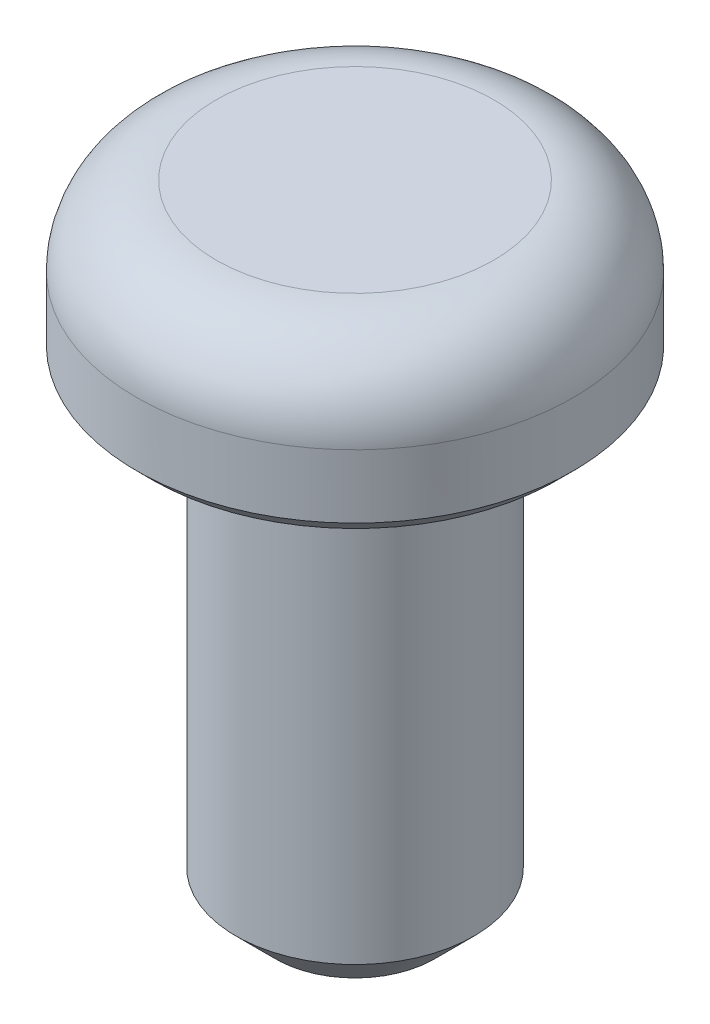
SolidWorks part; units mm, degrees
ref_plane "Front Plane" through (0, 0, 0) normal (0, 0, 1) x (1, 0, 0)
ref_plane "Top Plane" through (0, 0, 0) normal (0, 1, 0) x (1, 0, 0)
ref_plane "Right Plane" through (0, 0, 0) normal (1, 0, 0) x (0, 0, -1)
sketch "Sketch1" plane through (0, 0, 0) normal (0, 0, 1) x (1, 0, 0)
  line L0 (0, 0) -> (0, 8)
  line L1 (0, 8) -> (2.75, 8)
  line L2 (2.75, 8) -> (2.75, 6)
  line L3 (2.75, 6) -> (1.5, 6)
  line L4 (1.5, 6) -> (1.5, 0)
  line L5 (1.5, 0) -> (0, 0)
  dimension "D1" = 1.5
  dimension "D2" = 2.75
  dimension "D3" = 2
  dimension "D4" = 6
revolve "Revolve1" add sketch "Sketch1" angle 360 about L0
fillet "Fillet1" radius 1 1 edges at (0, 8, -2.75)
chamfer "Chamfer1" distance 0.5 angle 45 1 edges at (0, 0, -1.5)
chamfer "Chamfer2" distance 0.2 angle 45 1 edges at (0, 6, -2.75)
